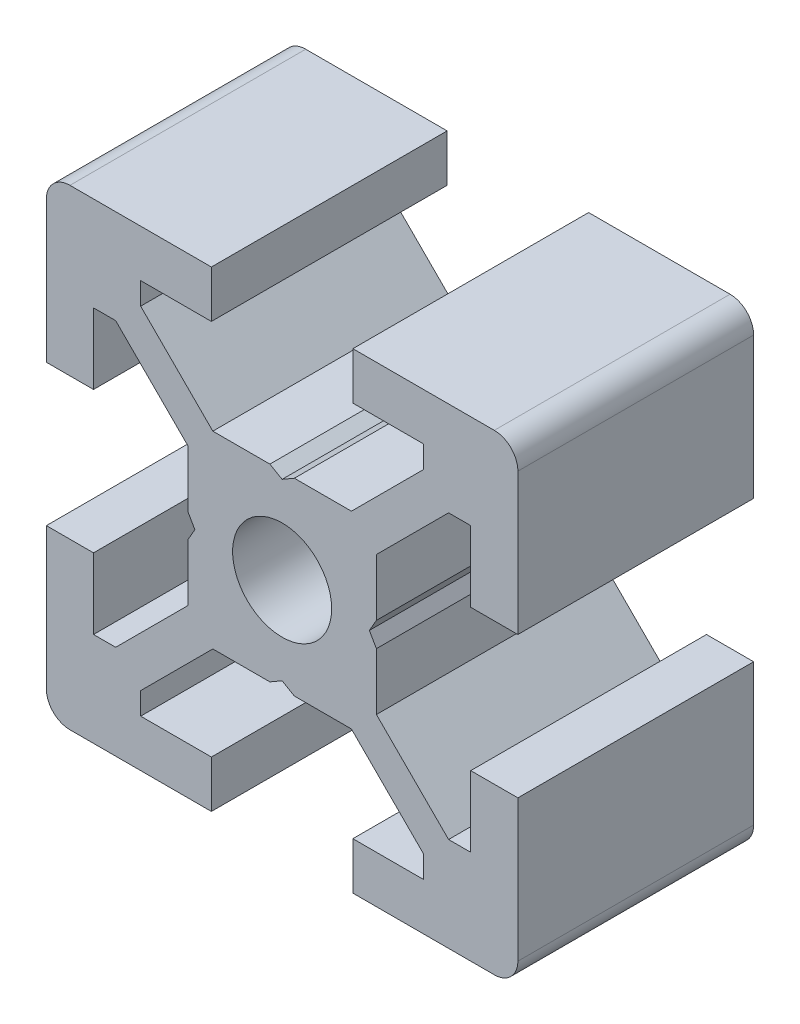
SolidWorks part; units mm, degrees
ref_plane "Front Plane" through (0, 0, 0) normal (0, 0, 1) x (1, 0, 0)
ref_plane "Top Plane" through (0, 0, 0) normal (0, 1, 0) x (1, 0, 0)
ref_plane "Right Plane" through (0, 0, 0) normal (1, 0, 0) x (0, 0, -1)
ref_plane "Plane1" through (0, 0, -500) normal (0, 0, -1) x (-1, 0, 0)
sketch "Sketch1" plane through (0, 0, -500) normal (0, 0, -1) x (-1, 0, 0)
  line L0 (9, 10) -> (3, 10)
  line L1 (3, 10) -> (3, 8)
  line L2 (3, 8) -> (6, 8)
  line L3 (6, 8) -> (6, 7.0607)
  line L4 (6, 7.0607) -> (2.9393, 4)
  line L5 (2.9393, 4) -> (0.5196, 4)
  line L6 (0.5196, 4) -> (0, 3.7)
  line L7 (0, 3.7) -> (-0.5196, 4)
  line L8 (-0.5196, 4) -> (-2.9393, 4)
  line L9 (-2.9393, 4) -> (-6, 7.0607)
  line L10 (-6, 7.0607) -> (-6, 8)
  line L11 (-6, 8) -> (-3, 8)
  line L12 (-3, 8) -> (-3, 10)
  line L13 (-3, 10) -> (-9, 10)
  line L14 (-10, 9) -> (-10, 3)
  line L15 (-10, 3) -> (-8, 3)
  line L16 (-8, 3) -> (-8, 6)
  line L17 (-8, 6) -> (-7.0607, 6)
  line L18 (-7.0607, 6) -> (-4, 2.9393)
  line L19 (-4, 2.9393) -> (-4, 0.5196)
  line L20 (-4, 0.5196) -> (-3.7, 0)
  line L21 (-3.7, 0) -> (-4, -0.5196)
  line L22 (-4, -0.5196) -> (-4, -2.9393)
  line L23 (-4, -2.9393) -> (-7.0607, -6)
  line L24 (-7.0607, -6) -> (-8, -6)
  line L25 (-8, -6) -> (-8, -3)
  line L26 (-8, -3) -> (-10, -3)
  line L27 (-10, -3) -> (-10, -9)
  line L28 (-9, -10) -> (-3, -10)
  line L29 (-3, -10) -> (-3, -8)
  line L30 (-3, -8) -> (-6, -8)
  line L31 (-6, -8) -> (-6, -7.0607)
  line L32 (-6, -7.0607) -> (-2.9393, -4)
  line L33 (-2.9393, -4) -> (-0.5196, -4)
  line L34 (-0.5196, -4) -> (0, -3.7)
  line L35 (0, -3.7) -> (0.5196, -4)
  line L36 (0.5196, -4) -> (2.9393, -4)
  line L37 (2.9393, -4) -> (6, -7.0607)
  line L38 (6, -7.0607) -> (6, -8)
  line L39 (6, -8) -> (3, -8)
  line L40 (3, -8) -> (3, -10)
  line L41 (3, -10) -> (9, -10)
  line L42 (10, -9) -> (10, -3)
  line L43 (10, -3) -> (8, -3)
  line L44 (8, -3) -> (8, -6)
  line L45 (8, -6) -> (7.0607, -6)
  line L46 (7.0607, -6) -> (4, -2.9393)
  line L47 (4, -2.9393) -> (4, -0.5196)
  line L48 (4, -0.5196) -> (3.7, 0)
  line L49 (3.7, 0) -> (4, 0.5196)
  line L50 (4, 0.5196) -> (4, 2.9393)
  line L51 (4, 2.9393) -> (7.0607, 6)
  line L52 (7.0607, 6) -> (8, 6)
  line L53 (8, 6) -> (8, 3)
  line L54 (8, 3) -> (10, 3)
  line L55 (10, 3) -> (10, 9)
  circle A0 centre (0, 0) radius 2.1
  arc A1 (10, 9) -> (9, 10) centre (9, 9) ccw
  arc A2 (-9, 10) -> (-10, 9) centre (-9, 9) ccw
  arc A3 (-10, -9) -> (-9, -10) centre (-9, -9) ccw
  arc A4 (9, -10) -> (10, -9) centre (9, -9) ccw
extrude "Boss-Extrude1" add sketch "Sketch1" against normal blind 10
